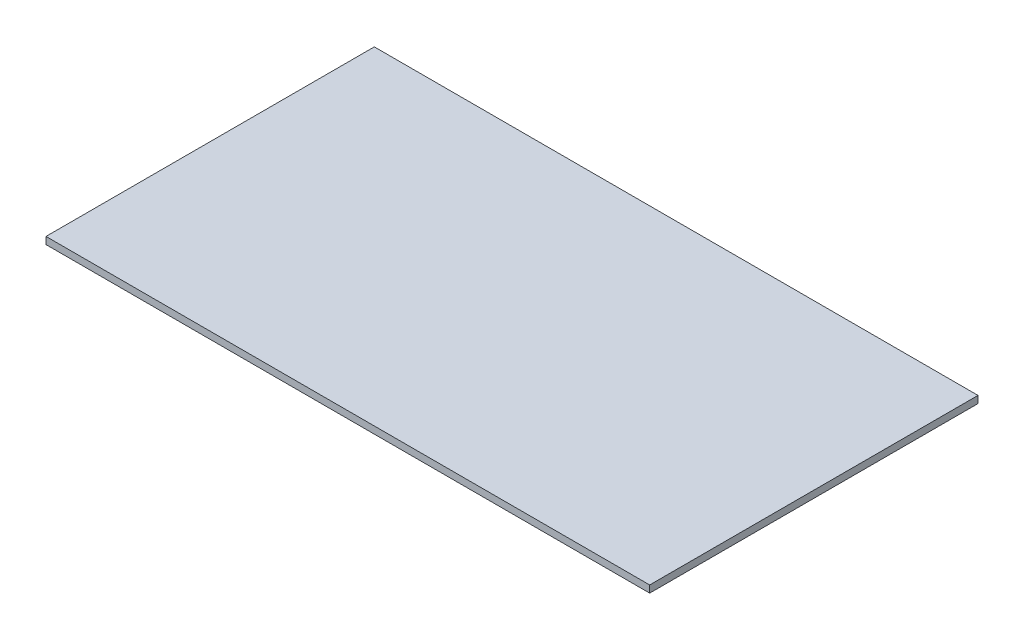
SolidWorks part; units mm, degrees
ref_plane "Front Plane" through (0, 0, 0) normal (0, 0, 1) x (1, 0, 0)
ref_plane "Top Plane" through (0, 0, 0) normal (0, 1, 0) x (1, 0, 0)
ref_plane "Right Plane" through (0, 0, 0) normal (1, 0, 0) x (0, 0, -1)
sketch "Sketch1" plane through (0, 0, 0) normal (0, 1, 0) x (1, 0, 0)
  line L0 (0, 155) -> (0, -155) construction
  line L1 (-285, -155) -> (285, -155)
  line L2 (-285, -155) -> (-285, 155)
  line L3 (-285, 155) -> (285, 155)
  line L4 (285, -155) -> (285, 155)
  line L5 (-285, -155) -> (285, 155) construction
  line L6 (-285, 155) -> (285, -155) construction
  line L7 (-285, 0) -> (285, 0) construction
  point P0 (0, 0)
  dimension "D1" = 310
  dimension "D2" = 570
extrude "Boss-Extrude1" add sketch "Sketch1" along normal blind 6.7
